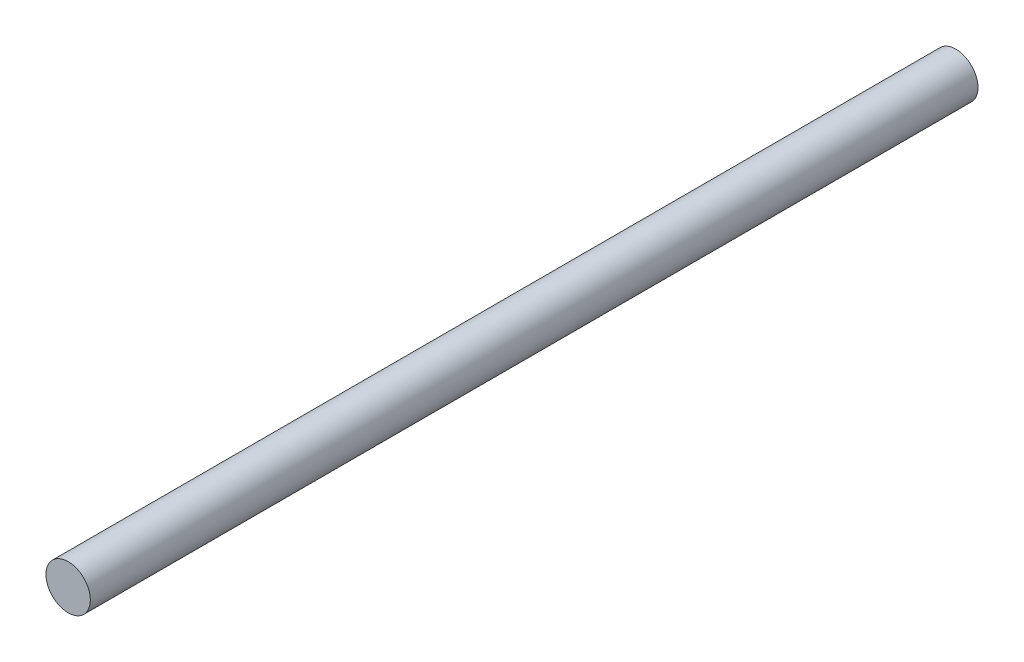
SolidWorks part; units mm, degrees
material "Pine"
ref_plane "Front Plane" through (0, 0, 0) normal (0, 0, 1) x (1, 0, 0)
ref_plane "Top Plane" through (0, 0, 0) normal (0, 1, 0) x (1, 0, 0)
ref_plane "Right Plane" through (0, 0, 0) normal (1, 0, 0) x (0, 0, -1)
sketch "Sketch1" plane through (0, 0, 0) normal (0, 0, 1) x (1, 0, 0)
  circle A0 centre (0, 0) radius 6.35
  dimension "D1" = 12.7
extrude "Boss-Extrude1" add sketch "Sketch1" along normal mid plane 254
